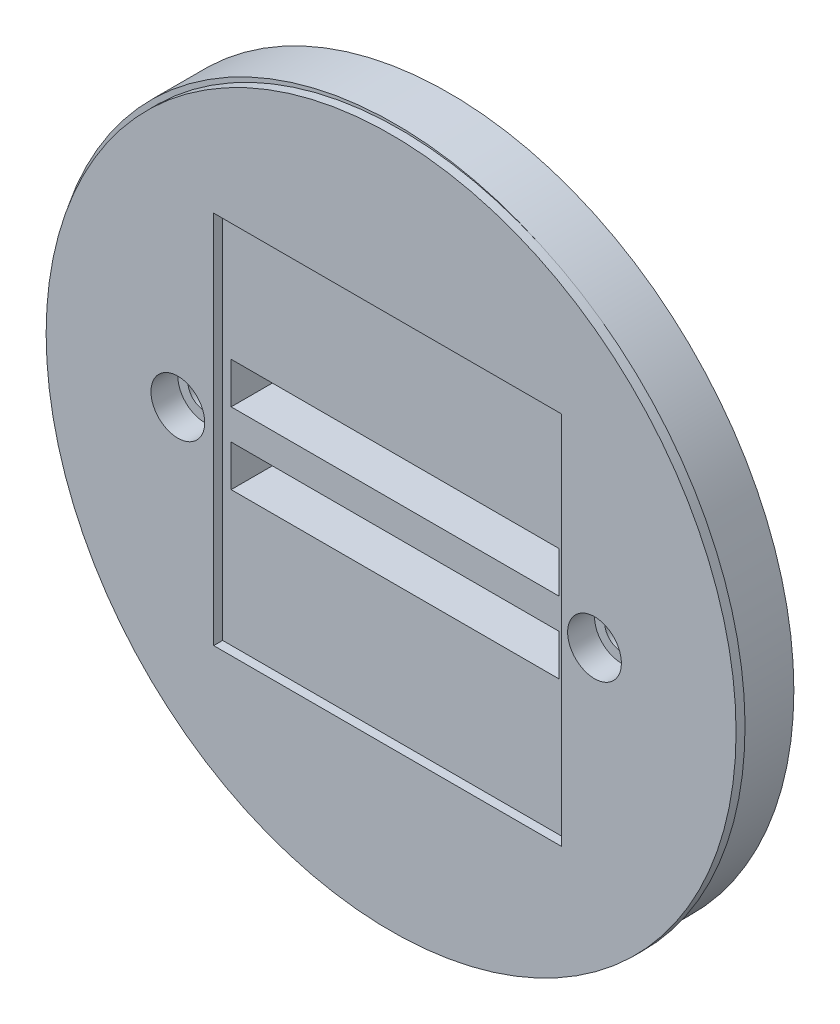
SolidWorks part; units mm, degrees
material "ABS"
ref_plane "Front Plane" through (0, 0, 0) normal (0, 0, 1) x (1, 0, 0)
ref_plane "Top Plane" through (0, 0, 0) normal (0, 1, 0) x (1, 0, 0)
ref_plane "Right Plane" through (0, 0, 0) normal (1, 0, 0) x (0, 0, -1)
sketch "Sketch1" plane through (0, 0, 0) normal (0, 0, 1) x (1, 0, 0)
  line L0 (18.3, 6.6) -> (18.3, 2)
  line L2 (-18.3, 6.6) -> (18.3, 6.6)
  line L3 (18.3, -1.4) -> (-18.3, -1.4)
  line L4 (-18.3, 2) -> (-18.3, 6.6)
  line L5 (-18.3, -1.4) -> (-18.3, -6)
  line L6 (-18.3, -6) -> (18.3, -6)
  line L7 (18.3, -6) -> (18.3, -1.4)
  line L8 (18.3, 2) -> (-18.3, 2)
  circle A0 centre (-23.25, 0) radius 1.875
  circle A1 centre (0, 0) radius 34.7 construction
  circle A2 centre (23.25, 0) radius 1.875
  circle A6 centre (0, 0) radius 38.5
  dimension "D2" = 69.4
  dimension "D5" = 77
  dimension "D10" = 3.75
  dimension "D8" = 3.75
  dimension "D3" = 18.3
  dimension "D4" = 23.25
  dimension "D6" = 18.3
  dimension "D7" = 23.25
  dimension "D9" = 4.6
extrude "Main Flange Coupling" add sketch "Sketch1" against normal blind 6
sketch "Sketch2" plane through (0, 0, 0) normal (0, 0, 1) x (1, 0, 0)
  line L0 (-19.25, 20.75) -> (19.55, 20.75)
  line L1 (-19.25, 20.75) -> (-19.25, -21.05)
  line L2 (-19.25, -21.05) -> (19.55, -21.05)
  line L3 (19.55, 20.75) -> (19.55, -21.05)
  line L4 (-19.25, 20.75) -> (19.55, -21.05) construction
  line L5 (-19.25, -21.05) -> (19.55, 20.75) construction
  circle A0 centre (0.55, -0.25) radius 38.5
  circle A1 centre (-23.25, 0) radius 1.65
  circle A2 centre (23.25, 0) radius 1.65
  dimension "D3" = 77
  dimension "D4" = 3.3
  dimension "D5" = 3.3
  dimension "D1" = 38.8
  dimension "D2" = 41.8
  dimension "D6" = 21
  dimension "D7" = 19
extrude "Boss-Extrude1" add sketch "Sketch2" along normal blind 1
sketch "Sketch3" plane through (0, 0, 1) normal (0, 0, 1) x (1, 0, 0)
  circle A0 centre (-23.25, 0) radius 3
  circle A1 centre (23.25, 0) radius 3
  dimension "D1" = 6
  dimension "D2" = 6
extrude "Cut-Extrude1" cut sketch "Sketch3" against normal blind 3
equation "\"D4@Sketch2\"= 3 + \"tol1@parametersSketch@prostheticParameters.SLDPRT\""
equation "\"D5@Sketch2\"= 3 + \"tol1@parametersSketch@prostheticParameters.SLDPRT\""
equation "\"D1@Sketch2\"= 38.5 + \"tol2@parametersSketch@prostheticParameters.SLDPRT\""
equation "\"D2@Sketch2\"= 41.5 + \"tol2@parametersSketch@prostheticParameters.SLDPRT\""
equation "\"D8@Sketch1\"= 3.45 + \"tol1@parametersSketch@prostheticParameters.SLDPRT\""
equation "\"D10@Sketch1\"= 3.45 + \"tol1@parametersSketch@prostheticParameters.SLDPRT\""
equation "\"D3@Sketch1\"= 18 + \"tol2@parametersSketch@prostheticParameters.SLDPRT\""
equation "\"D6@Sketch1\" = 18 + \"tol2@parametersSketch@prostheticParameters.SLDPRT\""
equation "\"D9@Sketch1\"= 4 + \"tol2@parametersSketch@prostheticParameters.SLDPRT\" * 2"
